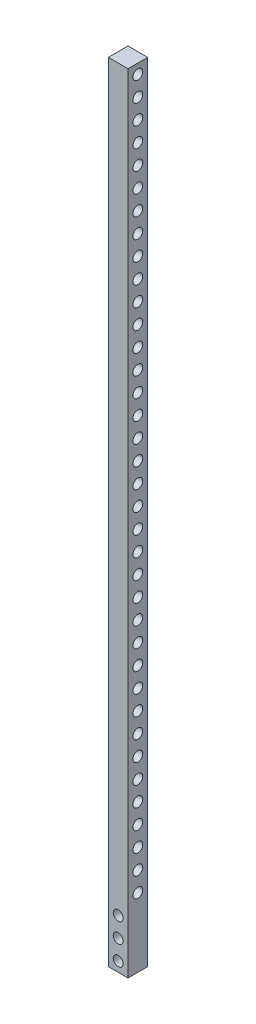
SolidWorks part; units mm, degrees
ref_plane "Plan de face" through (0, 0, 0) normal (0, 0, 1) x (1, 0, 0)
ref_plane "Plan de dessus" through (0, 0, 0) normal (0, 1, 0) x (1, 0, 0)
ref_plane "Plan de droite" through (0, 0, 0) normal (1, 0, 0) x (0, 0, -1)
sketch "Esquisse1" plane through (0, 0, 0) normal (1, 0, 0) x (0, 0, -1)
  line L1 (5, 200) -> (-5, 200)
  line L2 (5, 200) -> (5, -200)
  line L3 (5, -200) -> (-5, -200)
  line L4 (-5, 200) -> (-5, -200)
  line L5 (5, 200) -> (-5, -200) construction
  line L6 (5, -200) -> (-5, 200) construction
  circle A0 centre (0, 195) radius 2.5
  circle A1 centre (0, 185) radius 2.5
  circle A2 centre (0, 175) radius 2.5
  circle A3 centre (0, 165) radius 2.5
  circle A4 centre (0, 155) radius 2.5
  circle A5 centre (0, 145) radius 2.5
  circle A6 centre (0, 135) radius 2.5
  circle A7 centre (0, 125) radius 2.5
  circle A8 centre (0, 115) radius 2.5
  circle A9 centre (0, 105) radius 2.5
  circle A10 centre (0, 95) radius 2.5
  circle A11 centre (0, 85) radius 2.5
  circle A12 centre (0, 75) radius 2.5
  circle A13 centre (0, 65) radius 2.5
  circle A14 centre (0, 55) radius 2.5
  circle A15 centre (0, 45) radius 2.5
  circle A16 centre (0, 35) radius 2.5
  circle A17 centre (0, 25) radius 2.5
  circle A18 centre (0, 15) radius 2.5
  circle A19 centre (0, 5) radius 2.5
  circle A20 centre (0, -5) radius 2.5
  circle A21 centre (0, -15) radius 2.5
  circle A22 centre (0, -25) radius 2.5
  circle A23 centre (0, -35) radius 2.5
  circle A24 centre (0, -45) radius 2.5
  circle A25 centre (0, -55) radius 2.5
  circle A26 centre (0, -65) radius 2.5
  circle A27 centre (0, -75) radius 2.5
  circle A28 centre (0, -85) radius 2.5
  circle A29 centre (0, -95) radius 2.5
  circle A30 centre (0, -105) radius 2.5
  circle A31 centre (0, -115) radius 2.5
  circle A32 centre (0, -125) radius 2.5
  circle A33 centre (0, -135) radius 2.5
  circle A34 centre (0, -145) radius 2.5
  circle A35 centre (0, -155) radius 2.5
  circle A36 centre (0, -165) radius 2.5
  point P0 (0, 0)
  dimension "D3" = 5
  dimension "D1" = 10
  dimension "D2" = 400
  dimension "D4" = 5
  dimension "D5" = 37
extrude "BASE" add sketch "Esquisse1" along normal blind 10
sketch "Esquisse2" plane through (0, 0, 5) normal (0, 0, 1) x (1, 0, 0)
  line L0 (5, -200) -> (5, -157.227) construction
  line L1 (10, -200) -> (0, -200) construction
  circle A0 centre (5, -195) radius 2.5
  circle A1 centre (5, -185) radius 2.5
  circle A2 centre (5, -175) radius 2.5
  point P12 (0, 0)
  dimension "D1" = 5
  dimension "D2" = 5
  dimension "D3" = 5
  dimension "D4" = 5
  dimension "D5" = 10
  dimension "D6" = 10
extrude "Enlèv. mat.-Extru.1" cut sketch "Esquisse2" against normal blind 10
